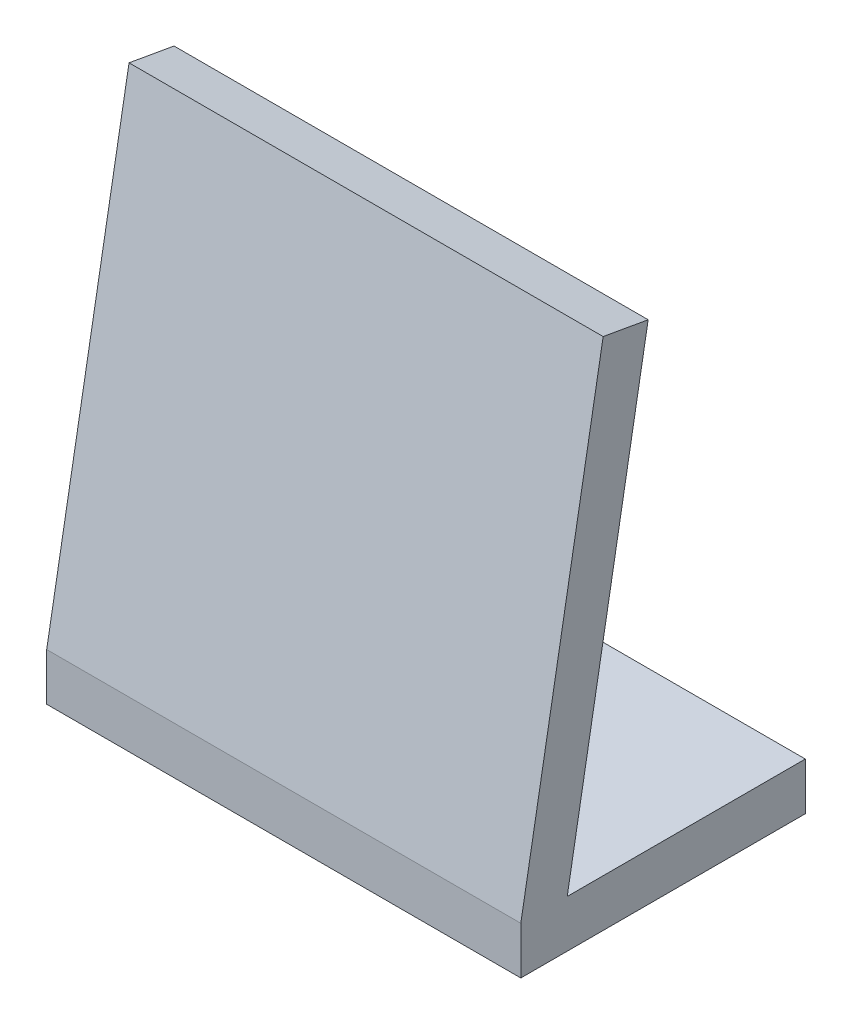
SolidWorks part; units mm, degrees
ref_plane "Front Plane" through (0, 0, 0) normal (0, 0, 1) x (1, 0, 0)
ref_plane "Top Plane" through (0, 0, 0) normal (0, 1, 0) x (1, 0, 0)
ref_plane "Right Plane" through (0, 0, 0) normal (1, 0, 0) x (0, 0, -1)
sketch "Sketch1" plane through (0, 0, 0) normal (0, 1, 0) x (1, 0, 0)
  line L1 (-12.5, 7.5) -> (12.5, 7.5)
  line L2 (-12.5, 7.5) -> (-12.5, -7.5)
  line L3 (-12.5, -7.5) -> (12.5, -7.5)
  line L4 (12.5, 7.5) -> (12.5, -7.5)
  point P4 (0, 7.5)
  point P6 (-12.5, 0)
  dimension "D1" = 15
  dimension "D2" = 25
extrude "Boss-Extrude1" add sketch "Sketch1" along normal blind 2.5
sketch "Sketch2" plane through (-12.5, 0, 0) normal (-1, 0, 0) x (0, 0, 1)
  line L0 (0.7856, 26.7017) -> (3.1588, 27.1202)
  line L1 (0.7856, 26.7017) -> (5.1268, 2.0815)
  line L2 (3.1588, 27.1202) -> (7.5, 2.5)
  line L3 (5.1268, 2.0815) -> (7.5, 2.5)
  line L4 (-7.5, 2.5) -> (7.5, 2.5) construction
  point P0 (0, 0)
  dimension "D1" = 80
  dimension "D2" = 25
extrude "Boss-Extrude2" add sketch "Sketch2" against normal through all
